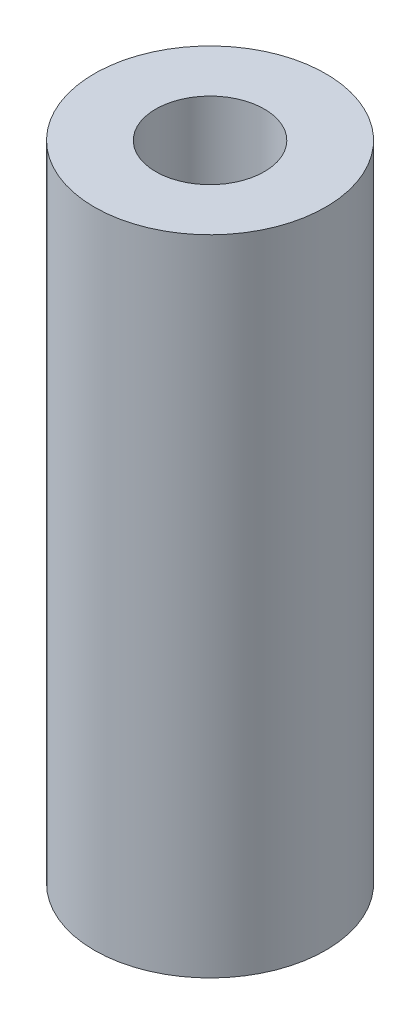
SolidWorks part; units mm, degrees
material "A-Glass Fiber"
ref_plane "Front Plane" through (0, 0, 0) normal (0, 0, 1) x (1, 0, 0)
ref_plane "Top Plane" through (0, 0, 0) normal (0, 1, 0) x (1, 0, 0)
ref_plane "Right Plane" through (0, 0, 0) normal (1, 0, 0) x (0, 0, -1)
sketch "Sketch1" plane through (0, 0, 0) normal (0, 1, 0) x (1, 0, 0)
  circle A0 centre (0, 0) radius 73.025
  circle A1 centre (0, 0) radius 34.29
  dimension "D1" = 146.05
  dimension "D2" = 68.58
extrude "Boss-Extrude1" add sketch "Sketch1" along normal blind 406.4
